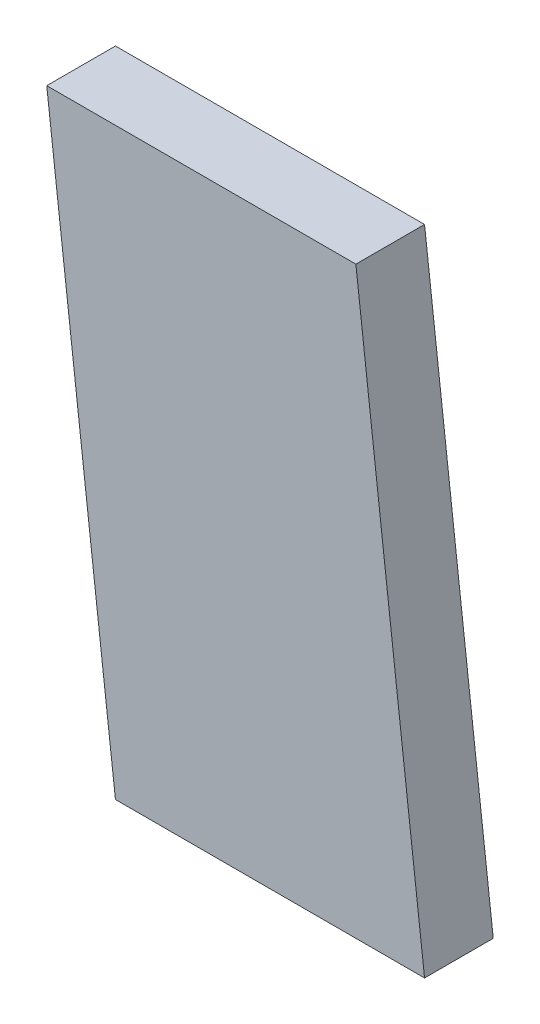
SolidWorks part; units mm, degrees
ref_plane "Front Plane" through (0, 0, 0) normal (0, 0, 1) x (1, 0, 0)
ref_plane "Top Plane" through (0, 0, 0) normal (0, 1, 0) x (1, 0, 0)
ref_plane "Right Plane" through (0, 0, 0) normal (1, 0, 0) x (0, 0, -1)
sketch "Sketch1" plane through (0, 0, 0) normal (0, 0, 1) x (1, 0, 0)
  line L0 (5200, 490) -> (5180, 660)
  line L1 (5180, 660) -> (5270, 660)
  line L2 (5270, 660) -> (5290, 490)
  line L3 (5290, 490) -> (5200, 490)
extrude "Boss-Extrude1" add sketch "Sketch1" along normal blind 20
